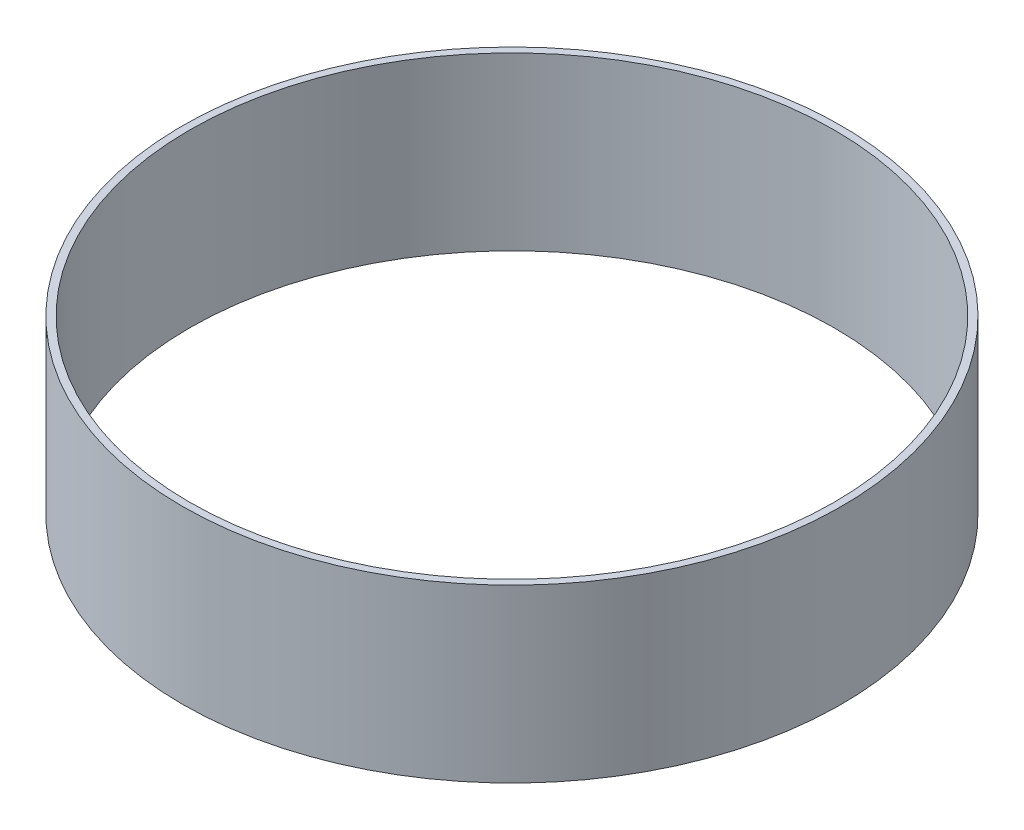
SolidWorks part; units mm, degrees
ref_plane "Front Plane" through (0, 0, 0) normal (0, 0, 1) x (1, 0, 0)
ref_plane "Top Plane" through (0, 0, 0) normal (0, 1, 0) x (1, 0, 0)
ref_plane "Right Plane" through (0, 0, 0) normal (1, 0, 0) x (0, 0, -1)
sketch "Sketch1" plane through (0, 0, 0) normal (0, 1, 0) x (1, 0, 0)
  circle A0 centre (-51.4376, 94.673) radius 67
  circle A1 centre (-51.4376, 94.673) radius 68.5
  circle A2 centre (-51.4376, 94.673) radius 67 construction
  circle A3 centre (-51.4376, 94.673) radius 67 construction
  dimension "D1" = 1.5
extrude "Boss-Extrude1" add sketch "Sketch1" along normal up to surface (35.625 mm away)
